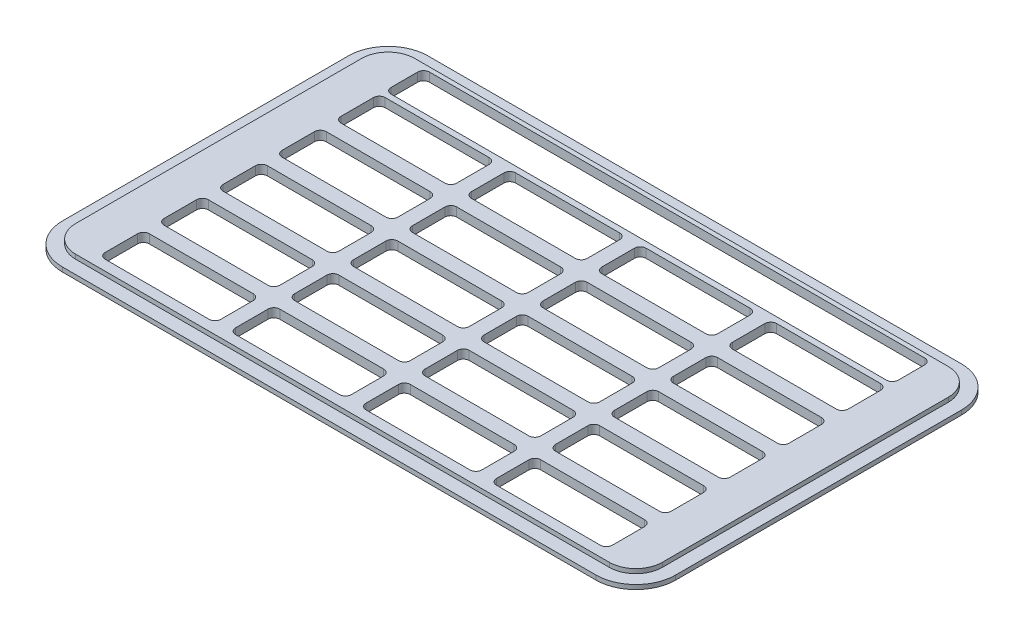
SolidWorks part; units mm, degrees
ref_plane "Front Plane" through (0, 0, 0) normal (0, 0, 1) x (1, 0, 0)
ref_plane "Top Plane" through (0, 0, 0) normal (0, 1, 0) x (1, 0, 0)
ref_plane "Right Plane" through (0, 0, 0) normal (1, 0, 0) x (0, 0, -1)
sketch "Sketch1" plane through (0, 0, 0) normal (0, 1, 0) x (1, 0, 0)
  line L1 (-104, -62) -> (104, -62)
  line L2 (-104, -62) -> (-104, 62)
  line L3 (-104, 62) -> (104, 62)
  line L4 (104, -62) -> (104, 62)
  line L5 (-104, -62) -> (104, 62) construction
  line L6 (-104, 62) -> (104, -62) construction
  point P0 (0, 0)
  dimension "D1" = 208
  dimension "D2" = 124
extrude "Outer Profile" add sketch "Sketch1" along normal blind 1.5
sketch "Sketch2" plane through (0, 1.5, 0) normal (0, 1, 0) x (1, 0, 0)
  line L1 (-99.5, -57.5) -> (99.5, -57.5)
  line L2 (-99.5, -57.5) -> (-99.5, 57.5)
  line L3 (-99.5, 57.5) -> (99.5, 57.5)
  line L4 (99.5, -57.5) -> (99.5, 57.5)
  line L5 (-99.5, -57.5) -> (99.5, 57.5) construction
  line L6 (-99.5, 57.5) -> (99.5, -57.5) construction
  point P0 (0, 0)
  dimension "D1" = 199
  dimension "D2" = 115
extrude "Inner Profile" add sketch "Sketch2" along normal blind 1.5
fillet "Fillet1" radius 9 4 edges at (99.5, 2.25, 57.5) (99.5, 2.25, -57.5) (-99.5, 2.25, -57.5) (-99.5, 2.25, 57.5)
fillet "Fillet2" radius 13.5 4 edges at (-104, 0.75, -62) (104, 0.75, -62) (104, 0.75, 62) (-104, 0.75, 62)
sketch "Sketch3" plane through (0, 3, 0) normal (0, 1, 0) x (1, 0, 0)
  line L1 (-86, -54) -> (86, -54) construction
  line L2 (-86, -54) -> (-86, 54) construction
  line L3 (-86, 54) -> (86, 54) construction
  line L4 (86, -54) -> (86, 54) construction
  line L5 (-86, -54) -> (86, 54) construction
  line L6 (-86, 54) -> (86, -54) construction
  point P0 (0, 0)
  dimension "D1" = 172
  dimension "D2" = 108
sketch "Sketch4" plane through (0, 3, 0) normal (0, 1, 0) x (1, 0, 0)
  line L0 (-86, -54) -> (-86, 54) construction
  line L1 (-86, 43) -> (86, 43)
  line L2 (-86, 43) -> (-86, 56)
  line L3 (-86, 56) -> (86, 56)
  line L4 (86, 43) -> (86, 56)
  line L10 (-86, 54) -> (86, 54) construction
  dimension "D1" = 2
  dimension "D2" = 11
  dimension "D3" = 172
extrude "Message Bar" cut sketch "Sketch4" against normal through all
sketch "Sketch5" plane through (0, 3, 0) normal (0, 1, 0) x (1, 0, 0)
  line L1 (-86, -54) -> (-68.875, -54)
  line L2 (-86, -54) -> (-86, -39)
  line L3 (-86, -39) -> (-68.875, -39)
  line L4 (-68.875, -54) -> (-68.875, -39)
  dimension "D1" = 17.125
  dimension "D2" = 15
extrude "Cutout" cut sketch "Sketch5" against normal through all
pattern_linear "Cutouts" count 8 spacing 22.125 along (1, 0, 0) count 5 spacing 20 along (0, 0, -1) of "Cutout"
fillet "Rads" radius 2 34 edges at (-63.875, 1.5, 39) (-41.75, 1.5, -21) (-19.625, 1.5, -21) (2.5, 1.5, -21) (24.625, 1.5, 19) (24.625, 1.5, 39) (86, 1.5, -41) (86, 1.5, -1) (41.75, 1.5, -21) (19.625, 1.5, -21) (-2.5, 1.5, -1) (-24.625, 1.5, -1) (-24.625, 1.5, -41) (-46.75, 1.5, -1) (-68.875, 1.5, 19) (-46.75, 1.5, 34) (-68.875, 1.5, 54) (-68.875, 1.5, -6) (-24.625, 1.5, 54) (-2.5, 1.5, 54) (19.625, 1.5, -6) (19.625, 1.5, 34) (41.75, 1.5, 14) (68.875, 1.5, -41) (24.625, 1.5, -41) (-86, 1.5, -41) (68.875, 1.5, -26) (2.5, 1.5, -6) (2.5, 1.5, 14) (2.5, 1.5, 54) (-19.625, 1.5, -6) (-41.75, 1.5, -6) (86, 1.5, -43) (86, 1.5, -56)
chamfer "Chamfer" [suppressed] distance 0.5 angle 45
sketch "Sketch6" plane through (0, 3, 0) normal (0, 1, 0) x (1, 0, 0)
  line L1 (-61.875, 41) -> (-70.875, 41)
  line L2 (-61.875, 41) -> (-61.875, 26)
  line L3 (-61.875, 26) -> (-70.875, 26)
  line L4 (-70.875, 41) -> (-70.875, 26)
extrude "Join" cut sketch "Sketch6" against normal through all
pattern_linear "LPattern1" count 4 spacing 44.25 along (1, 0, 0) count 5 spacing 20 along (0, 0, 1) of "Join"
